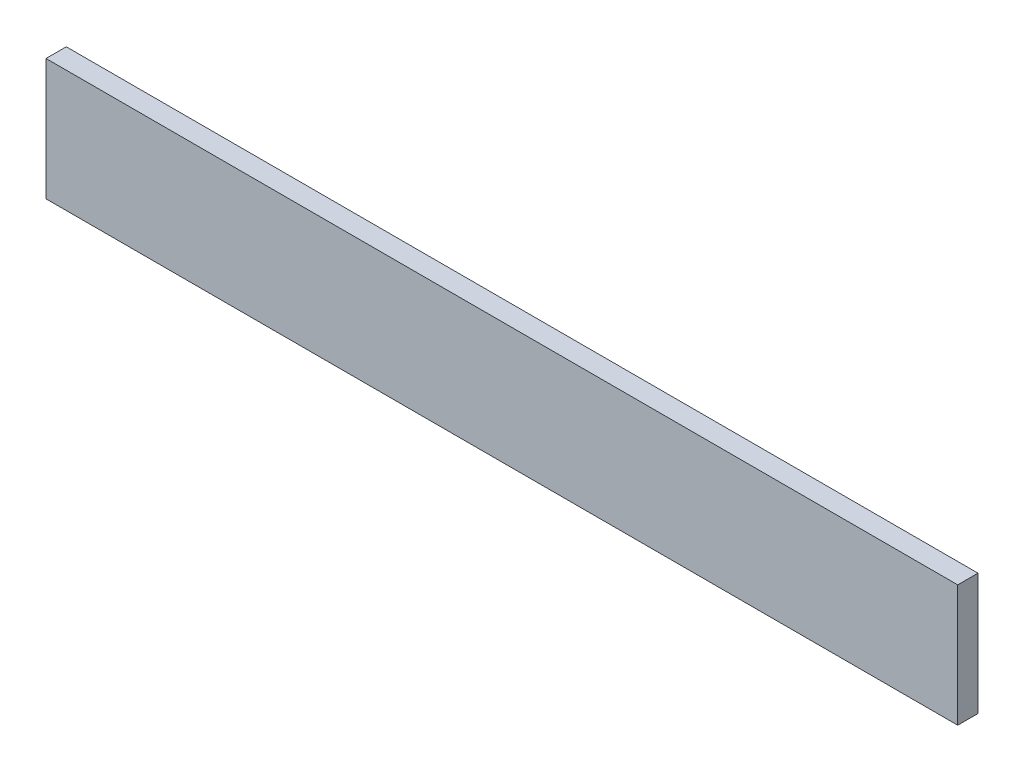
SolidWorks part; units mm, degrees
ref_plane "Front Plane" through (0, 0, 0) normal (0, 0, 1) x (1, 0, 0)
ref_plane "Top Plane" through (0, 0, 0) normal (0, 1, 0) x (1, 0, 0)
ref_plane "Right Plane" through (0, 0, 0) normal (1, 0, 0) x (0, 0, -1)
sketch "Sketch1" plane through (0, 0, 0) normal (0, 0, 1) x (1, 0, 0)
  line L7 (-112.5, 15) -> (112.5, 15)
  line L8 (-112.5, 15) -> (-112.5, -15)
  line L9 (-112.5, -15) -> (112.5, -15)
  line L10 (112.5, 15) -> (112.5, -15)
  line L11 (-112.5, 15) -> (112.5, -15) construction
  line L12 (-112.5, -15) -> (112.5, 15) construction
  point P0 (0, 0)
  dimension "D1" = 225
  dimension "D2" = 30
extrude "Boss-Extrude1" add sketch "Sketch1" along normal blind 5
